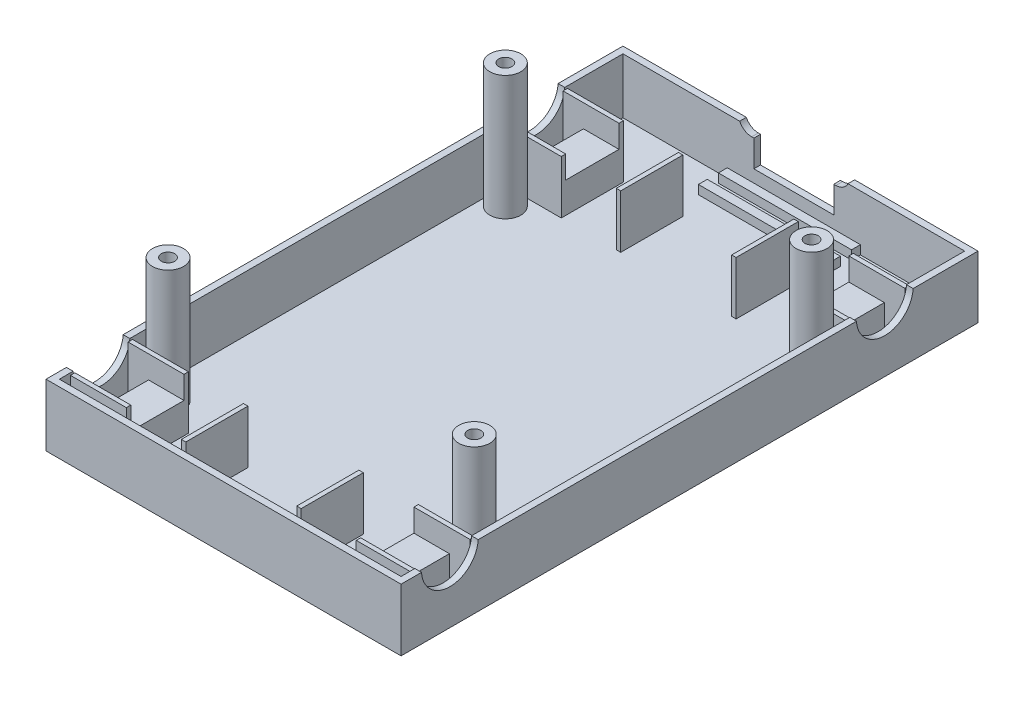
SolidWorks part; units mm, degrees
ref_plane "Спереди" through (0, 0, 0) normal (0, 0, 1) x (1, 0, 0)
ref_plane "Сверху" through (0, 0, 0) normal (0, 1, 0) x (1, 0, 0)
ref_plane "Справа" through (0, 0, 0) normal (1, 0, 0) x (0, 0, -1)
other "Configuration Table"
sketch "Корпус" plane through (0, 0, 0) normal (0, 1, 0) x (1, 0, 0)
  line L1 (40, -65) -> (-40, -65)
  line L2 (40, -65) -> (40, 65)
  line L3 (40, 65) -> (-40, 65)
  line L4 (-40, -65) -> (-40, 65)
  line L5 (40, -65) -> (-40, 65) construction
  line L6 (40, 65) -> (-40, -65) construction
  point P0 (0, 0)
  dimension "D1" = 80
  dimension "D2" = 130
sketch3d "Трехмерный эскиз1" plane through (0, 0, 0) normal (0, 0, 1) x (1, 0, 0)
extrude "Бобышка-Вытянуть1" add sketch "Корпус" along normal blind 14
sketch "Эскиз1" plane through (0, 14, 0) normal (0, 1, 0) x (1, 0, 0)
  line L0 (40, 65) -> (-40, 65) construction
  line L5 (-38.5, 63.5) -> (38.5, 63.5)
  line L6 (-38.5, 63.5) -> (-38.5, -63.5)
  line L7 (-38.5, -63.5) -> (38.5, -63.5)
  line L8 (38.5, 63.5) -> (38.5, -63.5)
  line L9 (-38.5, 63.5) -> (38.5, -63.5) construction
  line L10 (-38.5, -63.5) -> (38.5, 63.5) construction
  line L11 (-40, 65) -> (-40, -65) construction
  point P0 (0, 0)
  dimension "D1" = 1.5
  dimension "D2" = 1.5
extrude "Вырез-Вытянуть1" cut sketch "Эскиз1" against normal offset from surface (12.5 mm away) 1.5 up to face at (0, 0, 0)
sketch "Эскиз2" plane through (0, 0, -63.5) normal (0, 0, 1) x (1, 0, 0)
  line L19 (-12.5, 15.3) -> (12.5, 15.3) construction
  line L21 (-38.5, 1.5) -> (-38.5, 14) construction
  line L22 (38.5, 14) -> (-38.5, 14) construction
  line L23 (40, 14) -> (40, 0) construction
  line L24 (-40, 14) -> (40, 14) construction
  line L43 (14.3, 34.5) -> (-14.3, 34.5) construction
  line L56 (0, 34.5) -> (0, 5.5) construction
  line L58 (0, 5.5) -> (0, 34.5) construction
  line L59 (-14.3, 34.5) -> (-14.3, 5.5) construction
  line L60 (14.3, 5.5) -> (14.3, 34.5) construction
  line L61 (-14.3, 5.5) -> (14.3, 5.5) construction
  line L62 (-9, 18.3) -> (-9.5, 18.3)
  line L63 (-9, 24.3) -> (-9, 18.3)
  line L64 (9, 24.3) -> (-9, 24.3)
  line L65 (9, 18.3) -> (9, 24.3)
  line L66 (9.5, 18.3) -> (9, 18.3)
  line L67 (-9, 12.3) -> (-9.5, 12.3)
  line L68 (9, 12.3) -> (9.5, 12.3)
  line L69 (9, 6.3) -> (9, 12.3)
  line L70 (-9, 6.3) -> (9, 6.3)
  line L71 (-9, 12.3) -> (-9, 6.3)
  arc A14 (9.5, 12.3) -> (9.5, 18.3) centre (9.5, 15.3) ccw
  arc A15 (-9.5, 12.3) -> (-9.5, 18.3) centre (-9.5, 15.3) cw
  point P1 (0, 24.3)
  point P2 (-12.5, 15.3)
  point P5 (12.5, 15.3)
  dimension "D1" = 3
  dimension "D2" = 28.6
  dimension "D3" = 18
  dimension "D4" = 18
  dimension "D5" = 29
  dimension "D6" = 25
  dimension "D7" = 14.3
  dimension "D8" = 9.8
  dimension "D9" = 40
  dimension "D10" = 1.3
extrude "Вырез-Вытянуть2" cut sketch "Эскиз2" against normal blind 2
sketch "Эскиз3" plane through (-40, 0, 0) normal (-1, 0, 0) x (0, 0, 1)
  line L5 (-65, 0) -> (65, 0) construction
  line L6 (-65, 14) -> (-65, 0) construction
  line L20 (-44, 4.4) -> (-44, 36.6) construction
  line L21 (-50, 36.6) -> (-38, 4.4) construction
  line L22 (-50, 4.4) -> (-38, 36.6) construction
  line L23 (-38, 4.4) -> (-38, 36.6) construction
  line L24 (-50, 36.6) -> (-38, 36.6) construction
  line L25 (-50, 4.4) -> (-50, 36.6) construction
  line L26 (-50, 4.4) -> (-38, 4.4) construction
  line L27 (-40.8, 20.2) -> (-40.8, 19.9426)
  line L29 (-47.2, 20.2) -> (-47.2, 19.9426)
  arc A3 (-40.8, 19.9426) -> (-47.2, 19.9426) centre (-44, 14.4) cw
  arc A4 (-47.2, 20.2) -> (-40.8, 20.2) centre (-44, 20.2) cw
  point P0 (-49, 20.6)
  point P4 (-44, 23.4)
  point P6 (-44, 8)
  dimension "D3" = 32.2
  dimension "D4" = 10
  dimension "D5" = 12
  dimension "D1" = 3.2
  dimension "D2" = 6.4
  dimension "D6" = 4.4
  dimension "D7" = 5.8
  dimension "D8" = 15
sketch "Эскиз5" plane through (-40, 0, 0) normal (-1, 0, 0) x (0, 0, 1)
  line L2 (-65, 0) -> (65, 0) construction
  line L3 (54, 36.6) -> (54, 4.4) construction
  line L6 (65, 14) -> (65, 0) construction
  line L20 (54, 8.3) -> (54, 22.9) construction
  line L22 (48, 36.6) -> (60, 4.4) construction
  line L23 (48, 4.4) -> (60, 36.6) construction
  line L24 (60, 4.4) -> (60, 36.6) construction
  line L25 (48, 36.6) -> (60, 36.6) construction
  line L26 (48, 4.4) -> (48, 36.6) construction
  line L27 (48, 4.4) -> (60, 4.4) construction
  line L28 (57.1995, 20.1461) -> (57.1962, 19.9448)
  line L30 (50.8005, 20.1461) -> (50.8038, 19.9448)
  arc A2 (57.1962, 19.9448) -> (50.8038, 19.9448) centre (54, 14.4) cw
  arc A3 (50.8005, 20.1461) -> (57.1995, 20.1461) centre (54, 20.2) cw
  point P5 (49, 20.6)
  point P17 (54, 23.4)
  point P20 (54, 8)
  dimension "D1" = 6.4
  dimension "D2" = 3.2
  dimension "D5" = 12
  dimension "D6" = 4.4
  dimension "D3" = 5.8
  dimension "D4" = 10
  dimension "D7" = 32.2
  dimension "D8" = 5
sketch "Эскиз6" plane through (40, 0, 0) normal (1, 0, 0) x (0, 0, -1)
  line L0 (-65, 0) -> (65, 0) construction
  line L1 (-65, 14) -> (-65, 0) construction
  line L14 (-54, 4.4) -> (-54, 36.7) construction
  line L15 (-60, 36.7) -> (-48, 4.4) construction
  line L16 (-60, 4.4) -> (-48, 36.7) construction
  line L17 (-48, 4.4) -> (-48, 36.7) construction
  line L18 (-60, 36.7) -> (-48, 36.7) construction
  line L19 (-60, 4.4) -> (-60, 36.7) construction
  line L20 (-60, 4.4) -> (-48, 4.4) construction
  line L21 (-50.8, 20.2) -> (-50.8, 19.9426)
  line L22 (-57.2, 20.2) -> (-57.2, 19.9426)
  arc A2 (-50.8, 19.9426) -> (-57.2, 19.9426) centre (-54, 14.4) cw
  arc A3 (-57.2, 20.2) -> (-50.8, 20.2) centre (-54, 20.2) cw
  point P0 (-49, 20.6)
  point P9 (-54, 23.4)
  dimension "D5" = 5.8
  dimension "D6" = 4.4
  dimension "D1" = 6.4
  dimension "D2" = 3.2
  dimension "D3" = 12
  dimension "D4" = 10
  dimension "D7" = 5
sketch "Эскиз9" plane through (40, 0, 0) normal (1, 0, 0) x (0, 0, -1)
  line L0 (-65, 0) -> (65, 0) construction
  line L1 (65, 14) -> (65, 0) construction
  line L15 (44, 5.8) -> (44, 20.4) construction
  line L16 (44, 4.4) -> (44, 36.6) construction
  line L17 (38, 36.6) -> (50, 4.4) construction
  line L18 (38, 4.4) -> (50, 36.6) construction
  line L19 (50, 4.4) -> (50, 36.6) construction
  line L20 (38, 36.6) -> (50, 36.6) construction
  line L21 (38, 4.4) -> (38, 36.6) construction
  line L22 (38, 4.4) -> (50, 4.4) construction
  line L23 (47.2, 20.2) -> (47.2, 19.9426)
  line L25 (40.8, 20.2) -> (40.8, 19.9426)
  arc A2 (47.2, 19.9426) -> (40.8, 19.9426) centre (44, 14.4) cw
  arc A3 (40.8, 20.2) -> (47.2, 20.2) centre (44, 20.2) cw
  point P0 (49, 20.6)
  point P6 (44, 23.4)
  point P9 (44, 8)
  dimension "D5" = 32.2
  dimension "D6" = 4.4
  dimension "D1" = 3.2
  dimension "D3" = 6.4
  dimension "D2" = 12
  dimension "D4" = 10
  dimension "D7" = 5.8
  dimension "D8" = 15
sketch "Эскиз10" plane through (0, 1.5, 0) normal (0, 1, 0) x (1, 0, 0)
  line L0 (-40, 44) -> (40, 44) construction
  line L1 (-40, 65) -> (-40, -65) construction
  line L2 (40, -65) -> (40, 65) construction
  line L3 (-40, -54) -> (40, -54) construction
  line L4 (-12.2037, 65) -> (-40, 65) construction
  line L6 (-38.5, -63.5) -> (-38.5, 63.5) construction
  line L7 (-33.9, 38) -> (-25.9, 38)
  line L8 (-33.9, 38) -> (-33.9, 50)
  line L9 (-33.9, 50) -> (-25.9, 50)
  line L10 (-25.9, 38) -> (-25.9, 50)
  line L11 (-33.9, 38) -> (-25.9, 50) construction
  line L12 (-33.9, 50) -> (-25.9, 38) construction
  line L13 (25.9, 38) -> (33.9, 38)
  line L14 (25.9, 38) -> (25.9, 50)
  line L15 (25.9, 50) -> (33.9, 50)
  line L16 (33.9, 38) -> (33.9, 50)
  line L17 (25.9, 38) -> (33.9, 50) construction
  line L18 (25.9, 50) -> (33.9, 38) construction
  line L20 (-33.9, -60) -> (-25.9, -60)
  line L21 (-33.9, -60) -> (-33.9, -48)
  line L22 (-33.9, -48) -> (-25.9, -48)
  line L23 (-25.9, -60) -> (-25.9, -48)
  line L24 (-33.9, -60) -> (-25.9, -48) construction
  line L25 (-33.9, -48) -> (-25.9, -60) construction
  line L26 (25.9, -60) -> (33.9, -60)
  line L27 (25.9, -60) -> (25.9, -48)
  line L28 (25.9, -48) -> (33.9, -48)
  line L29 (33.9, -60) -> (33.9, -48)
  line L30 (25.9, -60) -> (33.9, -48) construction
  line L31 (25.9, -48) -> (33.9, -60) construction
  line L33 (38.5, -63.5) -> (38.5, 63.5) construction
  line L34 (38.5, -63.5) -> (38.5, 63.5) construction
  point P12 (-29.9, 44)
  point P19 (29.9, 44)
  point P27 (-29.9, -54)
  point P32 (29.9, -54)
  dimension "D1" = 12
  dimension "D2" = 4.6
  dimension "D3" = 8
  dimension "D4" = 8
  dimension "D5" = 12
  dimension "D6" = 4.6
  dimension "D7" = 12
  dimension "D8" = 8
  dimension "D9" = 8
  dimension "D10" = 12
  dimension "D11" = 4.6
  dimension "D12" = 4.6
  dimension "D13" = 21
  dimension "D14" = 98
extrude "Бобышка-Вытянуть2" add sketch "Эскиз10" along normal blind 6.9
sketch "Эскиз11" plane through (0, 1.5, 0) normal (0, 1, 0) x (1, 0, 0)
  line L0 (-25.9, 50) -> (-25.9, 51)
  line L1 (-25.9, 51) -> (-38.5, 51)
  line L2 (38.5, 50) -> (38.5, 51)
  line L3 (-25.9, 50) -> (-38.5, 50)
  line L4 (-38.5, 50) -> (-38.5, 51)
  line L5 (-25.9, 38) -> (-38.5, 38)
  line L6 (38.5, 51) -> (25.9, 51)
  line L7 (-38.5, 38) -> (-38.5, 37)
  line L8 (38.5, 50) -> (25.9, 50)
  line L9 (-38.5, 37) -> (-25.9, 37)
  line L10 (-25.9, 37) -> (-25.9, 38)
  line L11 (25.9, 50) -> (25.9, 51)
  line L12 (38.5, 38) -> (25.9, 38)
  line L13 (25.9, 38) -> (25.9, 37)
  line L14 (25.9, 37) -> (38.5, 37)
  line L15 (38.5, 37) -> (38.5, 38)
  line L16 (38.5, -48) -> (38.5, -47)
  line L17 (38.5, -47) -> (25.9, -47)
  line L18 (38.5, -48) -> (25.9, -48)
  line L19 (25.9, -48) -> (25.9, -47)
  line L20 (38.5, -60) -> (25.9, -60)
  line L21 (25.9, -60) -> (25.9, -61)
  line L22 (25.9, -61) -> (38.5, -61)
  line L23 (38.5, -61) -> (38.5, -60)
  line L24 (-25.9, -48) -> (-25.9, -47)
  line L25 (-25.9, -47) -> (-38.5, -47)
  line L26 (-25.9, -48) -> (-38.5, -48)
  line L27 (-38.5, -48) -> (-38.5, -47)
  line L28 (-25.9, -60) -> (-38.5, -60)
  line L29 (-38.5, -60) -> (-38.5, -61)
  line L30 (-38.5, -61) -> (-25.9, -61)
  line L31 (-25.9, -61) -> (-25.9, -60)
  dimension "D1" = 1
  dimension "D2" = 12.6
  dimension "D3" = 12.6
  dimension "D4" = 1
  dimension "D5" = 12.6
  dimension "D6" = 1
  dimension "D7" = 12.6
  dimension "D8" = 1
extrude "Бобышка-Вытянуть3" add sketch "Эскиз11" along normal blind 12
sketch "Эскиз13" plane through (0, 1.5, 0) normal (0, 1, 0) x (1, 0, 0)
  line L4 (-34.5, -43) -> (34.5, -43) construction
  line L6 (0, 65) -> (0, -65) construction
  line L7 (-9, 65) -> (9, 65) construction
  line L8 (-40, -65) -> (40, -65) construction
  line L10 (-40, 0) -> (40, 0) construction
  line L11 (-40, 65) -> (-40, -65) construction
  line L12 (40, -65) -> (40, 65) construction
  circle A8 centre (-34.5, 33) radius 3.5
  circle A9 centre (34.5, 33) radius 3.5
  circle A10 centre (-34.5, -43) radius 3.5
  circle A11 centre (34.5, -43) radius 3.5
  point P1 (0, -43)
  dimension "D5" = 69
  dimension "D6" = 69
  dimension "D26" = 7
  dimension "D28" = 7
  dimension "D30" = 7
  dimension "D1" = 76
  dimension "D4" = 22
  dimension "D7" = 76
extrude "Бобышка-Вытянуть4" add sketch "Эскиз13" along normal blind 28
extrude "Вырез-Вытянуть9" cut sketch "Эскиз5" against normal up to surface (1.5 mm away) up to face at (-38.5, 7.55, 4)
extrude "Вырез-Вытянуть10" cut sketch "Эскиз6" against normal up to surface (1.5 mm away) up to face at (38.5, 7.55, 4)
extrude "Вырез-Вытянуть11" cut sketch "Эскиз3" against normal up to surface (1.5 mm away) up to face at (-38.5, 8.4285, -20.6949)
extrude "Вырез-Вытянуть12" cut sketch "Эскиз9" against normal up to surface (1.5 mm away) up to face at (38.5, 8.4285, -20.6949)
sketch "Эскиз15" plane through (0, 29.5, 0) normal (0, 1, 0) x (1, 0, 0)
  circle A0 centre (-34.5, 33) radius 1.5
  circle A1 centre (34.5, 33) radius 1.5
  circle A2 centre (34.5, -43) radius 1.5
  circle A3 centre (-34.5, -43) radius 1.5
  dimension "D1" = 3
  dimension "D2" = 3
  dimension "D3" = 3
  dimension "D4" = 3
extrude "Вырез-Вытянуть14" cut sketch "Эскиз15" against normal offset from surface (19.5 mm away) 10 up to face at (0, 0, 0)
sketch "Эскиз16" plane through (0, 1.5, 0) normal (0, 1, 0) x (1, 0, 0)
  line L0 (0, 65) -> (0, -65) construction
  line L1 (-15, 63.5) -> (15, 63.5)
  line L2 (-15, 63.5) -> (-15, 61.5)
  line L3 (-15, 61.5) -> (15, 61.5)
  line L4 (15, 63.5) -> (15, 61.5)
  line L5 (-15, 63.5) -> (15, 61.5) construction
  line L6 (-15, 61.5) -> (15, 63.5) construction
  line L7 (-38.5, 63.5) -> (38.5, 63.5) construction
  line L9 (-15, 59) -> (15, 59)
  line L10 (-15, 59) -> (-15, 57)
  line L11 (-15, 57) -> (15, 57)
  line L12 (15, 59) -> (15, 57)
  line L13 (-15, 59) -> (15, 57) construction
  line L14 (-15, 57) -> (15, 59) construction
  point P0 (0, 62.5)
  point P7 (0, 63.5)
  point P10 (0, 58)
  dimension "D1" = 30
  dimension "D2" = 2
  dimension "D3" = 2
  dimension "D4" = 30
  dimension "D5" = 2.5
extrude "Бобышка-Вытянуть5" add sketch "Эскиз16" along normal blind 2
sketch "Эскиз17" plane through (0, 1.5, 0) normal (0, 1, 0) x (1, 0, 0)
  line L0 (-13.5, 51) -> (-12.5, 51)
  line L1 (-13.5, 51) -> (-13.5, 37)
  line L2 (-13.5, 37) -> (-12.5, 37)
  line L3 (-12.5, 51) -> (-12.5, 37)
  line L4 (-13.5, 51) -> (-12.5, 37) construction
  line L5 (-13.5, 37) -> (-12.5, 51) construction
  line L6 (12.5, 51) -> (13.5, 51)
  line L7 (12.5, 51) -> (12.5, 37)
  line L8 (12.5, 37) -> (13.5, 37)
  line L9 (13.5, 51) -> (13.5, 37)
  line L10 (12.5, 51) -> (13.5, 37) construction
  line L11 (12.5, 37) -> (13.5, 51) construction
  line L12 (-13.5, -47) -> (-12.5, -47)
  line L13 (-13.5, -47) -> (-13.5, -61)
  line L14 (-13.5, -61) -> (-12.5, -61)
  line L15 (-12.5, -47) -> (-12.5, -61)
  line L16 (-13.5, -47) -> (-12.5, -61) construction
  line L17 (-13.5, -61) -> (-12.5, -47) construction
  line L18 (12.5, -47) -> (13.5, -47)
  line L19 (12.5, -47) -> (12.5, -61)
  line L20 (12.5, -61) -> (13.5, -61)
  line L21 (13.5, -47) -> (13.5, -61)
  line L22 (12.5, -47) -> (13.5, -61) construction
  line L23 (12.5, -61) -> (13.5, -47) construction
  line L24 (-40, 44) -> (40, 44) construction
  line L25 (-40, 50.3875) -> (-40, 37.6125) construction
  line L26 (40, 37.6125) -> (40, 50.3875) construction
  line L27 (-40, -47.6125) -> (-40, -60.3875) construction
  line L28 (-40, -54) -> (40, -54) construction
  line L29 (40, -60.3875) -> (40, -47.6125) construction
  line L33 (-38.5, 37.6125) -> (-38.5, -47.6125) construction
  line L34 (38.5, -47.6125) -> (38.5, 37.6125) construction
  line L35 (38.5, 50.3875) -> (38.5, 63.5) construction
  line L36 (-38.5, 63.5) -> (-38.5, 50.3875) construction
  point P0 (-13, 44)
  point P5 (13, 44)
  point P10 (-13, -54)
  point P15 (13, -54)
  point P32 (0, 0)
  point P33 (0, 0)
  point P34 (0, 0)
  point P35 (0, 0)
  dimension "D1" = 14
  dimension "D2" = 1
  dimension "D3" = 14
  dimension "D4" = 1
  dimension "D5" = 14
  dimension "D6" = 1
  dimension "D7" = 14
  dimension "D8" = 1
  dimension "D9" = 25
  dimension "D10" = 25
  dimension "D11" = 25
  dimension "D12" = 25
extrude "Бобышка-Вытянуть6" add sketch "Эскиз17" along normal blind 12
